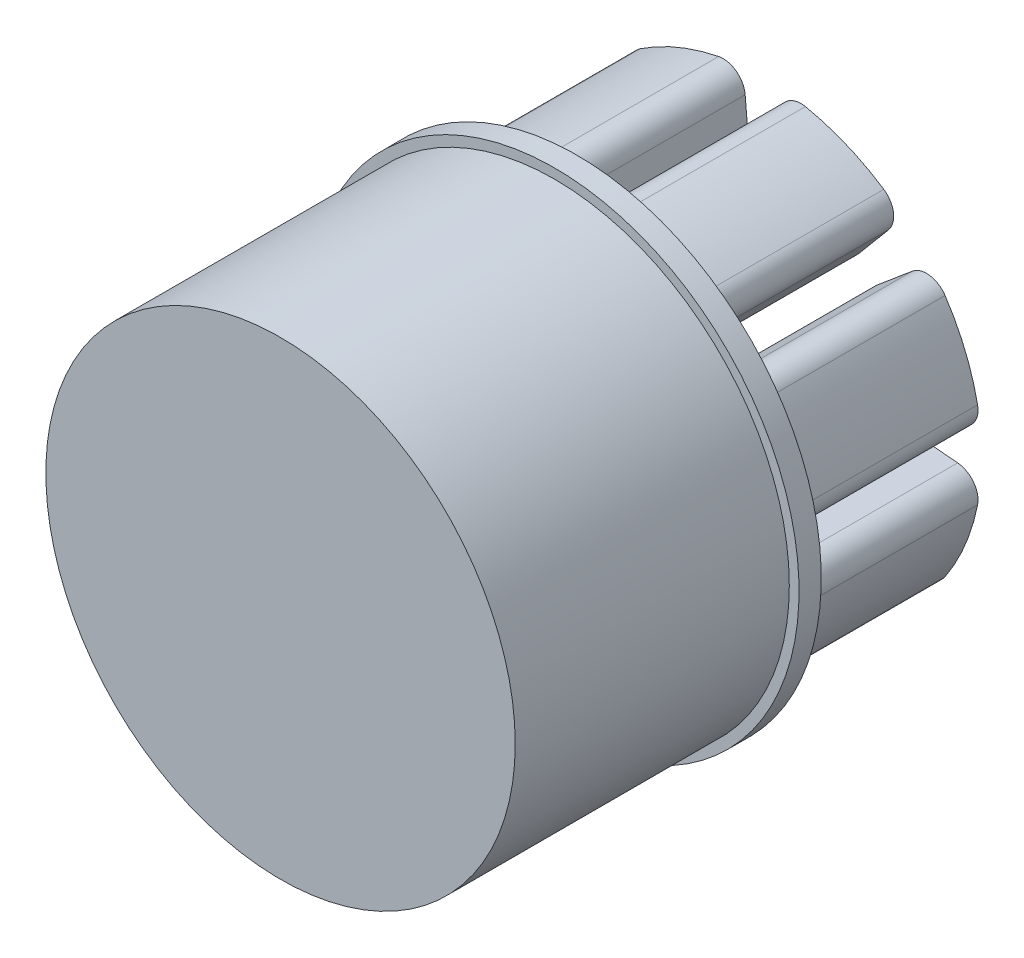
SolidWorks part; units mm, degrees
ref_plane "Front Plane" through (0, 0, 0) normal (0, 0, 1) x (1, 0, 0)
ref_plane "Top Plane" through (0, 0, 0) normal (0, 1, 0) x (1, 0, 0)
ref_plane "Right Plane" through (0, 0, 0) normal (1, 0, 0) x (0, 0, -1)
sketch "Sketch1" plane through (0, 0, 0) normal (0, 0, 1) x (-1, 0, 0)
  line L3 (-1.7382, 20.2047) -> (-2.2728, 26.4182)
  line L6 (1.7382, 20.2047) -> (2.2728, 26.4182)
  line L7 (13.0577, 15.516) -> (17.0734, 20.2876)
  line L8 (15.516, 13.0577) -> (20.2876, 17.0734)
  line L9 (20.2047, 1.7382) -> (26.4182, 2.2728)
  line L10 (20.2047, -1.7382) -> (26.4182, -2.2728)
  line L11 (15.516, -13.0577) -> (20.2876, -17.0734)
  line L12 (13.0577, -15.516) -> (17.0734, -20.2876)
  line L13 (1.7382, -20.2047) -> (2.2728, -26.4182)
  line L14 (-1.7382, -20.2047) -> (-2.2728, -26.4182)
  line L15 (-13.0577, -15.516) -> (-17.0734, -20.2876)
  line L16 (-15.516, -13.0577) -> (-20.2876, -17.0734)
  line L17 (-20.2047, -1.7382) -> (-26.4182, -2.2728)
  line L18 (-20.2047, 1.7382) -> (-26.4182, 2.2728)
  line L19 (-15.516, 13.0577) -> (-20.2876, 17.0734)
  line L20 (-13.0577, 15.516) -> (-17.0734, 20.2876)
  arc A1 (-24.7173, 16.4395) -> (-29.1022, 5.8533) centre (0, 0) ccw
  arc A11 (-5.8533, 29.1022) -> (-16.4395, 24.7173) centre (0, 0) ccw
  arc A12 (16.4395, 24.7173) -> (5.8533, 29.1022) centre (0, 0) ccw
  arc A13 (29.1022, 5.8533) -> (24.7173, 16.4395) centre (0, 0) ccw
  arc A14 (24.7173, -16.4395) -> (29.1022, -5.8533) centre (0, 0) ccw
  arc A15 (5.8533, -29.1022) -> (16.4395, -24.7173) centre (0, 0) ccw
  arc A16 (-16.4395, -24.7173) -> (-5.8533, -29.1022) centre (0, 0) ccw
  arc A17 (-29.1022, -5.8533) -> (-24.7173, -16.4395) centre (0, 0) ccw
  arc A18 (26.4182, 2.2728) -> (29.1022, 5.8533) centre (26.1611, 5.2617) ccw
  arc A19 (26.4182, -2.2728) -> (29.1022, -5.8533) centre (26.1611, -5.2617) cw
  arc A20 (20.2876, -17.0734) -> (24.7173, -16.4395) centre (22.2193, -14.7781) ccw
  arc A21 (17.0734, -20.2876) -> (16.4395, -24.7173) centre (14.7781, -22.2193) cw
  arc A22 (2.2728, -26.4182) -> (5.8533, -29.1022) centre (5.2617, -26.1611) ccw
  arc A23 (-2.2728, -26.4182) -> (-5.8533, -29.1022) centre (-5.2617, -26.1611) cw
  arc A24 (-17.0734, -20.2876) -> (-16.4395, -24.7173) centre (-14.7781, -22.2193) ccw
  arc A25 (-20.2876, -17.0734) -> (-24.7173, -16.4395) centre (-22.2193, -14.7781) cw
  arc A26 (-26.4182, -2.2728) -> (-29.1022, -5.8533) centre (-26.1611, -5.2617) ccw
  arc A27 (-26.4182, 2.2728) -> (-29.1022, 5.8533) centre (-26.1611, 5.2617) cw
  arc A28 (-20.2876, 17.0734) -> (-24.7173, 16.4395) centre (-22.2193, 14.7781) ccw
  arc A29 (-17.0734, 20.2876) -> (-16.4395, 24.7173) centre (-14.7781, 22.2193) cw
  arc A30 (20.2876, 17.0734) -> (24.7173, 16.4395) centre (22.2193, 14.7781) cw
  arc A31 (17.0734, 20.2876) -> (16.4395, 24.7173) centre (14.7781, 22.2193) ccw
  arc A32 (2.2728, 26.4182) -> (5.8533, 29.1022) centre (5.2617, 26.1611) cw
  arc A33 (-2.2728, 26.4182) -> (-5.8533, 29.1022) centre (-5.2617, 26.1611) ccw
  arc A35 (17.0284, 4.0354) -> (14.8943, 9.1874) centre (0, 0) ccw
  arc A36 (14.8943, -9.1874) -> (17.0284, -4.0354) centre (0, 0) ccw
  arc A37 (4.0354, -17.0284) -> (9.1874, -14.8943) centre (0, 0) ccw
  arc A38 (-9.1874, -14.8943) -> (-4.0354, -17.0284) centre (0, 0) ccw
  arc A39 (-17.0284, -4.0354) -> (-14.8943, -9.1874) centre (0, 0) ccw
  arc A40 (-14.8943, 9.1874) -> (-17.0284, 4.0354) centre (0, 0) ccw
  arc A41 (-4.0354, 17.0284) -> (-9.1874, 14.8943) centre (0, 0) ccw
  arc A42 (9.1874, 14.8943) -> (4.0354, 17.0284) centre (0, 0) ccw
  arc A43 (-13.0577, 15.516) -> (-9.1874, 14.8943) centre (-10.7624, 17.4477) ccw
  arc A44 (-1.7382, 20.2047) -> (-4.0354, 17.0284) centre (-4.7272, 19.9475) cw
  arc A45 (1.7382, 20.2047) -> (4.0354, 17.0284) centre (4.7272, 19.9475) ccw
  arc A46 (13.0577, 15.516) -> (9.1874, 14.8943) centre (10.7624, 17.4477) cw
  arc A47 (15.516, 13.0577) -> (14.8943, 9.1874) centre (17.4477, 10.7624) ccw
  arc A48 (20.2047, 1.7382) -> (17.0284, 4.0354) centre (19.9475, 4.7272) cw
  arc A49 (20.2047, -1.7382) -> (17.0284, -4.0354) centre (19.9475, -4.7272) ccw
  arc A50 (15.516, -13.0577) -> (14.8943, -9.1874) centre (17.4477, -10.7624) cw
  arc A51 (13.0577, -15.516) -> (9.1874, -14.8943) centre (10.7624, -17.4477) ccw
  arc A52 (1.7382, -20.2047) -> (4.0354, -17.0284) centre (4.7272, -19.9475) cw
  arc A53 (-1.7382, -20.2047) -> (-4.0354, -17.0284) centre (-4.7272, -19.9475) ccw
  arc A54 (-13.0577, -15.516) -> (-9.1874, -14.8943) centre (-10.7624, -17.4477) cw
  arc A55 (-15.516, -13.0577) -> (-14.8943, -9.1874) centre (-17.4477, -10.7624) ccw
  arc A56 (-20.2047, -1.7382) -> (-17.0284, -4.0354) centre (-19.9475, -4.7272) cw
  arc A57 (-20.2047, 1.7382) -> (-17.0284, 4.0354) centre (-19.9475, 4.7272) ccw
  arc A58 (-15.516, 13.0577) -> (-14.8943, 9.1874) centre (-17.4477, 10.7624) cw
  point P5 (35.8651, 1.3412)
  point P41 (0, 0)
  point P49 (0, 0)
  point P72 (-2.5444, 29.5758)
  point P73 (-1.5, 17.4356)
  point P77 (1.5, 17.4356)
  dimension "D1" = 29.685
  dimension "D2" = 3
  dimension "D6" = 3
  dimension "D8" = 35
  dimension "D3" = 1.5
  dimension "D4" = 1.5
  dimension "D5" = 8
sketch "Sketch2" plane through (0, 0, 0) normal (0, 0, 1) x (1, 0, 0)
  circle A0 centre (0, 0) radius 14.5
  circle A1 centre (0, 0) radius 17.5
  dimension "D1" = 29
  dimension "D2" = 3
extrude "Boss-Extrude1" add sketch "Sketch1" along normal blind 25
sketch "Sketch5" plane through (0, 0, 0) normal (0, 1, 0) x (1, 0, 0)
  line L0 (0, -25) -> (31.685, -25) construction
  line L1 (5.8533, -25) -> (16.4395, -25) construction
  line L2 (17.5, -25) -> (31.685, -25)
  line L3 (31.685, -25) -> (31.685, -65)
  line L4 (31.685, -65) -> (0, -65)
  line L5 (0, -65) -> (0, -55.2029)
  line L6 (17.5, -25) -> (17.5, -37.7029)
  line L7 (8.5, -53) -> (0, -53) construction
  arc A1 (17.5, -37.7029) -> (0, -55.2029) centre (0, -37.7029) cw
  point P10 (0, 0)
  point P11 (0, 0)
  dimension "D1" = 31.685
  dimension "D2" = 17.5
  dimension "D3" = 40
  dimension "D4" = 28
  dimension "D5" = 8.5
revolve "Revolve1" add sketch "Sketch5" angle 360 about L5
sketch "Sketch6" plane through (0, 0, 25) normal (0, 0, -1) x (-1, 0, 0)
  circle A0 centre (0, 0) radius 33
  circle A1 centre (0, 0) radius 31.685
  dimension "D1" = 66
  dimension "D2" = 63.37
extrude "Boss-Extrude2" add sketch "Sketch6" against normal blind 3
